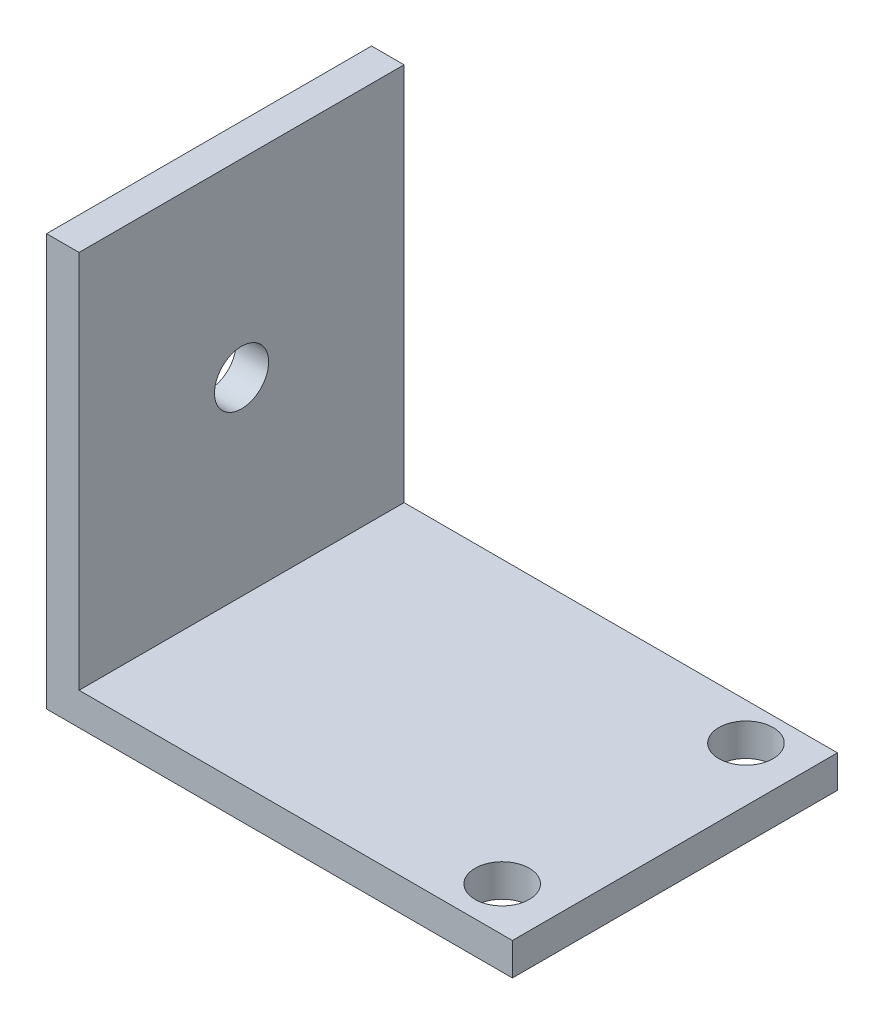
SolidWorks part; units mm, degrees
ref_plane "Front Plane" through (0, 0, 0) normal (0, 0, 1) x (1, 0, 0)
ref_plane "Top Plane" through (0, 0, 0) normal (0, 1, 0) x (1, 0, 0)
ref_plane "Right Plane" through (0, 0, 0) normal (1, 0, 0) x (0, 0, -1)
other "Configuration Table"
sketch "Sketch1" plane through (0, 0, 0) normal (0, 0, 1) x (1, 0, 0)
  line L0 (0, 0) -> (0, 70)
  line L1 (0, 0) -> (80, 0)
  dimension "D1" = 70
  dimension "D2" = 80
extrude "Extrude-Thin1" add sketch "Sketch1" along normal blind 60 thin thin type one direction wall 6
sketch "Sketch2" plane through (0, 0, 0) normal (0, 1, 0) x (1, 0, 0)
  line L0 (80, -60) -> (80, 0) construction
  circle A0 centre (70, -6.8877) radius 5
  circle A1 centre (70, -51.8877) radius 5
  dimension "D1" = 10
  dimension "D3" = 45
  dimension "D2" = 10
extrude "Cut-Extrude1" cut sketch "Sketch2" against normal through all
sketch "Sketch3" plane through (0, 0, 0) normal (1, 0, 0) x (0, 0, -1)
  line L0 (0, 70) -> (0, 0) construction
  line L1 (-60, 0) -> (0, 0) construction
  circle A0 centre (-30, 35) radius 5
  point P4 (-30, 0)
  dimension "D1" = 10
  dimension "D3" = 35
  dimension "D2" = 30
extrude "Cut-Extrude2" cut sketch "Sketch3" against normal through all
